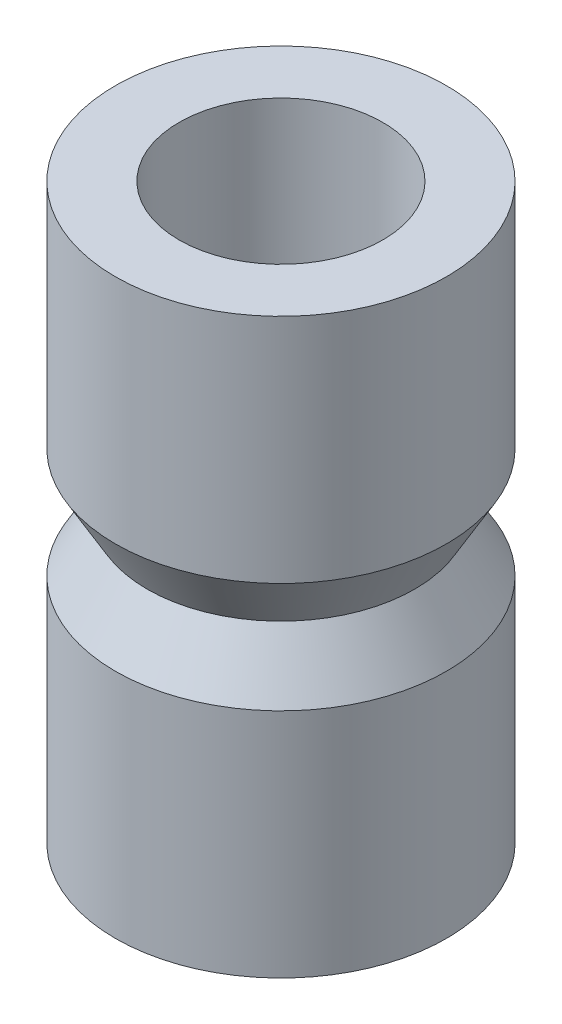
SolidWorks part; units mm, degrees
ref_plane "前视基准面" through (0, 0, 0) normal (0, 0, 1) x (1, 0, 0)
ref_plane "上视基准面" through (0, 0, 0) normal (0, 1, 0) x (1, 0, 0)
ref_plane "右视基准面" through (0, 0, 0) normal (1, 0, 0) x (0, 0, -1)
sketch "草图1" plane through (0, 0, 0) normal (0, 1, 0) x (1, 0, 0)
  circle A0 centre (0, 0) radius 1.6
  circle A1 centre (0, 0) radius 2.6
  dimension "D1" = 3.2
  dimension "D2" = 1
extrude "凸台-拉伸1" add sketch "草图1" along normal blind 9
sketch "草图2" plane through (0, 0, 0) normal (0, 0, 1) x (1, 0, 0)
  line L0 (-2.6, 4.5) -> (4.173, 4.5) construction
  line L1 (-2.6, 9) -> (-2.6, 0) construction
  line L2 (-2.6, 5.366) -> (-2.1, 4.5)
  line L3 (-2.1, 4.5) -> (-2.6, 3.634)
  line L4 (-2.6, 3.634) -> (-2.6, 5.366)
  dimension "D1" = 30
  dimension "D2" = 30
  dimension "D3" = 0.5
ref_axis "基准轴1" through (0, 9, 0) along (0, -1, 0)
revolve "切除-旋转1" cut sketch "草图2" angle 360 about axis through (0, 9, 0) along (0, -1, 0)
